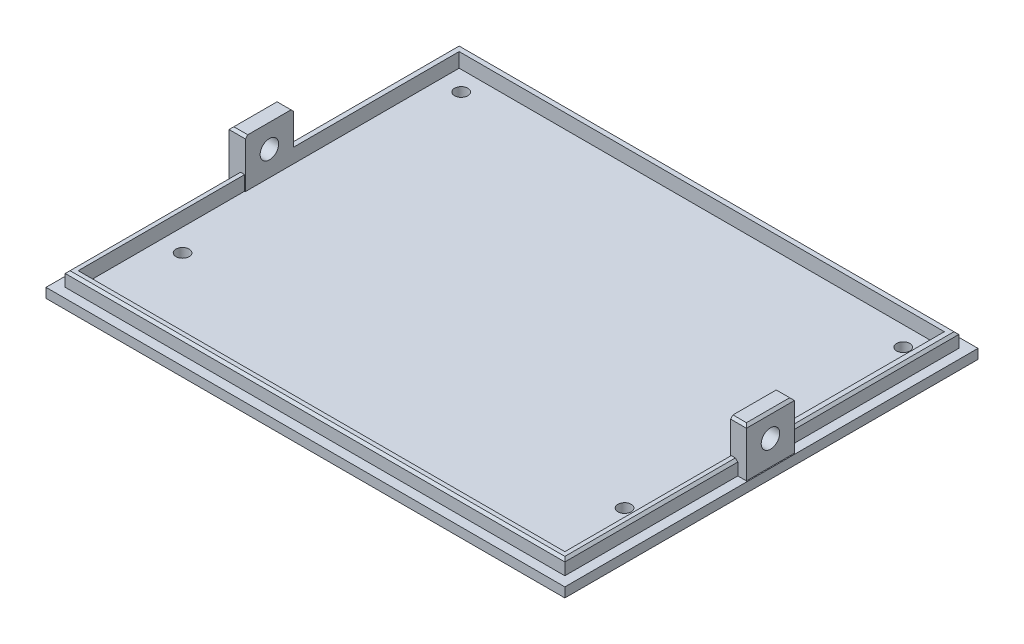
SolidWorks part; units mm, degrees
material "ABS"
ref_plane "Front Plane" through (0, 0, 0) normal (0, 0, 1) x (1, 0, 0)
ref_plane "Top Plane" through (0, 0, 0) normal (0, 1, 0) x (1, 0, 0)
ref_plane "Right Plane" through (0, 0, 0) normal (1, 0, 0) x (0, 0, -1)
sketch "Sketch1" plane through (0, 0, 0) normal (0, 1, 0) x (1, 0, 0)
  line L1 (0, 0) -> (108, 0)
  line L2 (0, 0) -> (0, 86)
  line L3 (0, 86) -> (108, 86)
  line L4 (108, 0) -> (108, 86)
  dimension "D1" = 86
  dimension "D2" = 108
extrude "Boss-Extrude1" add sketch "Sketch1" along normal blind 2
sketch "Sketch2" plane through (0, 2, 0) normal (0, 1, 0) x (1, 0, 0)
  line L0 (2, 84) -> (2, 2)
  line L1 (2, 2) -> (106, 2)
  line L2 (106, 2) -> (106, 84)
  line L3 (106, 84) -> (2, 84)
  line L16 (104.5, 82.5) -> (3.5, 82.5)
  line L17 (3.5, 82.5) -> (3.5, 3.5)
  line L18 (3.5, 3.5) -> (104.5, 3.5)
  line L19 (104.5, 3.5) -> (104.5, 82.5)
  line L20 (0, 0) -> (108, 0) construction
  line L21 (0, 86) -> (0, 0) construction
  line L22 (108, 86) -> (0, 86) construction
  line L23 (108, 0) -> (108, 86) construction
  dimension "D1" = 2
  dimension "D2" = 2
  dimension "D3" = 2
  dimension "D5" = 2
  dimension "D4" = 1.5
extrude "Boss-Extrude2" add sketch "Sketch2" along normal blind 3
sketch "Sketch5" plane through (2, 0, 0) normal (-1, 0, 0) x (0, 0, 1)
  line L0 (-43, -10.8667) -> (-43, 16.6425) construction
  line L1 (-86, 2) -> (0, 2) construction
  line L2 (-48, 2) -> (-38, 2)
  line L3 (-48, 2) -> (-48, 12)
  line L4 (-48, 12) -> (-38, 12)
  line L5 (-38, 2) -> (-38, 12)
  point P9 (-43, 12)
  dimension "D1" = 43
  dimension "D2" = 10
  dimension "D3" = 10
extrude "Boss-Extrude4" add sketch "Sketch5" along normal up to surface and the other way up to surface up to face at (0, 1, -43) other way up to face at (3.5, 3.5, -43)
ref_plane "Plane1" through (54, 0, 0) normal (-1, 0, 0) x (0, 0, 1)
sketch "Sketch6" plane through (106, 0, 0) normal (1, 0, 0) x (0, 0, -1)
  line L0 (0, 2) -> (86, 2) construction
  line L1 (38, 2) -> (48, 2)
  line L2 (38, 2) -> (38, 12)
  line L3 (38, 12) -> (48, 12)
  line L4 (48, 2) -> (48, 12)
  line L5 (2, 2) -> (84, 2) construction
  point P8 (43, 2)
  point P9 (43, 2)
  dimension "D1" = 10
  dimension "D2" = 10
extrude "Boss-Extrude5" add sketch "Sketch6" along normal up to surface and the other way up to surface up to face at (108, 1, -43) other way up to face at (104.5, 3.5, -43)
sketch "Sketch11" plane through (0, 12, 0) normal (0, 1, 0) x (1, 0, 0)
  line L0 (0.1, 38) -> (0.1, 48)
  line L1 (107.8, 38) -> (107.8, 48)
  line L4 (3.5, 48) -> (0, 48)
  line L5 (0, 48) -> (0, 38)
  line L6 (0, 38) -> (3.5, 38)
  line L7 (3.5, 38) -> (3.5, 48)
  line L8 (0.1, 48) -> (0, 48)
  line L9 (0, 48) -> (0, 38)
  line L10 (0, 38) -> (0.1, 38)
  line L13 (104.5, 38) -> (108, 38)
  line L14 (108, 38) -> (108, 48)
  line L15 (108, 48) -> (104.5, 48)
  line L16 (104.5, 48) -> (104.5, 38)
  line L17 (107.8, 38) -> (108, 38)
  line L18 (108, 38) -> (108, 48)
  line L19 (108, 48) -> (107.8, 48)
  dimension "D2" = 0.1
  dimension "D4" = 0.2
  dimension "D1" = 0
  dimension "D3" = 0
extrude "Cut-Extrude2" cut sketch "Sketch11" against normal up to surface (10 mm away) up to face at (54, 2, -66.5)
chamfer "Chamfer1" distance 0.5 angle 45 6 edges at (106, 5, -20) (54, 5, -2) (106, 5, -66) (54, 5, -84) (2, 5, -66) (2, 5, -20)
chamfer "Chamfer2" distance 0.5 angle 45 6 edges at (1.8, 12, -48) (0.1, 12, -43) (1.8, 12, -38) (106.15, 12, -48) (106.15, 12, -38) (107.8, 12, -43)
sketch "Sketch12" plane through (0, 0, 0) normal (0, -1, 0) x (1, 0, 0)
  arc A0 (9.375, -20.425) -> (6.625, -20.425) centre (8, -20.425) ccw construction
  arc A1 (9.375, -78.425) -> (6.625, -78.425) centre (8, -78.425) ccw construction
  arc A2 (101.375, -20.425) -> (98.625, -20.425) centre (100, -20.425) ccw construction
  arc A3 (98.625, -78.425) -> (101.375, -78.425) centre (100, -78.425) ccw construction
  circle A8 centre (100, -78.425) radius 1.375
  circle A9 centre (8, -78.425) radius 1.375
  circle A10 centre (8, -20.425) radius 1.375
  circle A11 centre (100, -20.425) radius 1.375
  dimension "D1" = 2.75
extrude "Cut-Extrude3" cut sketch "Sketch12" against normal up to next
sketch "Sketch13" plane through (0, 5, 0) normal (0, 1, 0) x (1, 0, 0)
  line L0 (3.35, 3.35) -> (104.65, 3.35)
  line L1 (104.65, 3.35) -> (104.65, 82.65)
  line L2 (104.65, 82.65) -> (3.35, 82.65)
  line L3 (3.35, 82.65) -> (3.35, 3.35)
  line L4 (3.5, 3.5) -> (104.5, 3.5)
  line L5 (104.5, 3.5) -> (104.5, 82.5)
  line L6 (104.5, 82.5) -> (3.5, 82.5)
  line L7 (3.5, 82.5) -> (3.5, 3.5)
  line L10 (104.5, 82.5) -> (3.5, 82.5)
  line L12 (3.5, 82.5) -> (3.5, 3.5) construction
  line L13 (3.5, 3.5) -> (104.5, 3.5) construction
  line L14 (104.5, 3.5) -> (104.5, 82.5) construction
  dimension "D1" = 0
  dimension "D2" = 0.15
extrude "Cut-Extrude5" cut sketch "Sketch13" against normal up to surface (3 mm away)
sketch "Sketch14" plane through (0.1, 0, 0) normal (-1, 0, 0) x (0, 0, 1)
  circle A2 centre (-43, 7.15) radius 1.925 construction
  circle A3 centre (-43, 7.15) radius 1.925
extrude "Cut-Extrude6" cut sketch "Sketch14" against normal up to next
sketch "Sketch15" plane through (107.8, 0, 0) normal (1, 0, 0) x (0, 0, -1)
  circle A2 centre (43, 7.15) radius 1.925 construction
  circle A3 centre (43, 7.15) radius 1.925
extrude "Cut-Extrude7" cut sketch "Sketch15" against normal up to next
equation "\"A\"= 115 - 3.5 * 2"
equation "\"B\"= 86"
equation "\"D1@Sketch1\"=\"B\""
equation "\"D2@Sketch1\"=\"A\""
